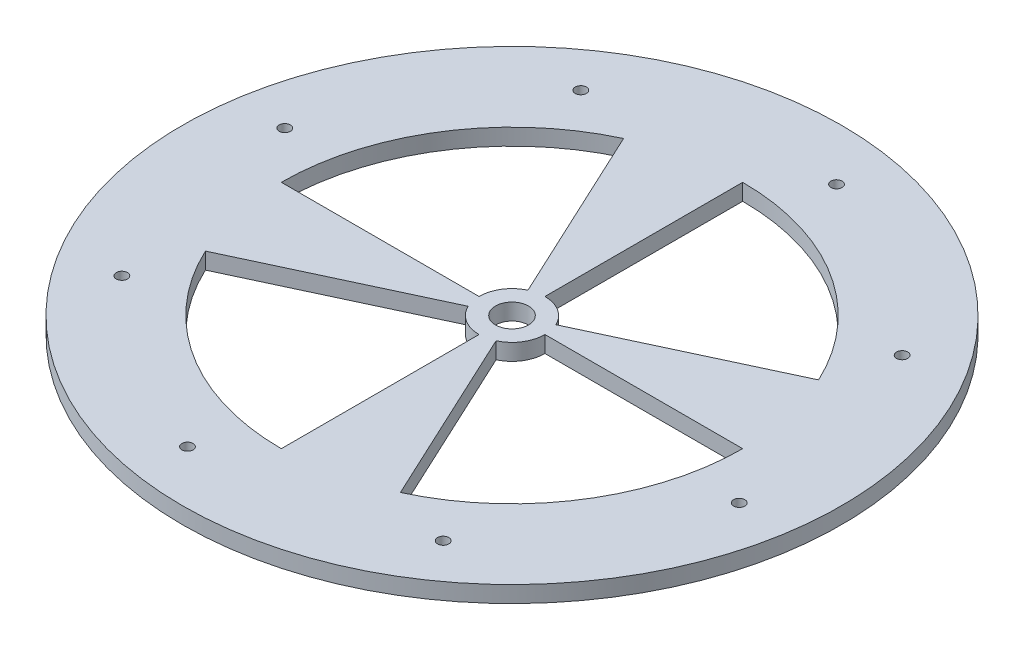
SolidWorks part; units mm, degrees
material "1023 Carbon Steel Sheet (SS)"
ref_plane "Front Plane" through (0, 0, 0) normal (0, 0, 1) x (1, 0, 0)
ref_plane "Top Plane" through (0, 0, 0) normal (0, 1, 0) x (1, 0, 0)
ref_plane "Right Plane" through (0, 0, 0) normal (1, 0, 0) x (0, 0, -1)
sketch "Sketch1" plane through (0, 0, 0) normal (0, 1, 0) x (1, 0, 0)
  line L0 (0, 25.4) -> (0, 177.8)
  line L1 (23.0202, 10.7345) -> (161.1415, 75.1415)
  line L2 (10.7345, -23.0202) -> (75.1415, -161.1415)
  line L3 (25.4, 0) -> (177.8, 0)
  line L4 (-23.0202, -10.7345) -> (-161.1415, -75.1415)
  line L5 (0, -25.4) -> (0, -177.8)
  line L6 (-10.7345, 23.0202) -> (-75.1415, 161.1415)
  line L7 (-25.4, 0) -> (-177.8, 0)
  line L8 (-161.1415, -75.1415) -> (-230.2022, -107.345) construction
  line L9 (-176.8549, -123.8352) -> (0, 0) construction
  circle A0 centre (0, 0) radius 254
  circle A1 centre (0, 0) radius 12.7
  arc A2 (161.1415, 75.1415) -> (0, 177.8) centre (0, 0) ccw
  arc A3 (75.1415, -161.1415) -> (177.8, 0) centre (0, 0) ccw
  arc A4 (-161.1415, -75.1415) -> (0, -177.8) centre (0, 0) ccw
  arc A5 (-75.1415, 161.1415) -> (-177.8, 0) centre (0, 0) ccw
  circle A6 centre (37.4906, 212.62) radius 4.318
  circle A7 centre (176.8549, 123.8352) radius 4.318
  circle A8 centre (212.62, -37.4906) radius 4.318
  circle A9 centre (123.8352, -176.8549) radius 4.318
  circle A10 centre (-37.4906, -212.62) radius 4.318
  circle A11 centre (-176.8549, -123.8352) radius 4.318
  arc A12 (-10.7345, 23.0202) -> (-25.4, 0) centre (0, 0) ccw
  arc A13 (23.0202, 10.7345) -> (0, 25.4) centre (0, 0) ccw
  arc A14 (10.7345, -23.0202) -> (25.4, 0) centre (0, 0) ccw
  arc A15 (-23.0202, -10.7345) -> (0, -25.4) centre (0, 0) ccw
  circle A16 centre (-212.62, 37.4906) radius 4.318
  circle A17 centre (-123.8352, 176.8549) radius 4.318
  point P23 (0, 0)
  point P35 (0, 0)
  dimension "D1" = 4
  dimension "D2" = 8
  dimension "D3" = 254
  dimension "D4" = 12.7
  dimension "D5" = 25.4
  dimension "D6" = 177.8
  dimension "D7" = 8.636
  dimension "D8" = 25
  dimension "D9" = 215.9
  dimension "D10" = 10
extrude "Boss-Extrude3" add sketch "Sketch1" along normal blind 12.7
